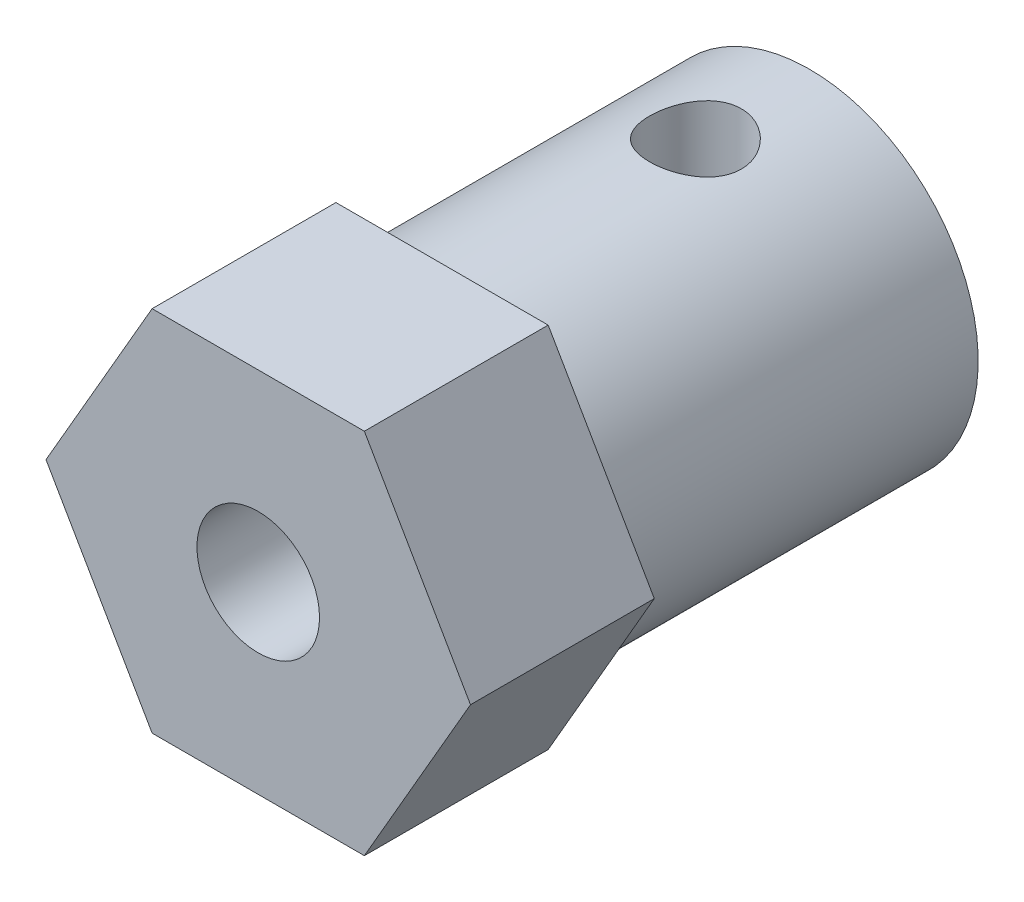
SolidWorks part; units mm, degrees
material "合金钢"
ref_plane "前视基准面" through (0, 0, 0) normal (0, 0, 1) x (1, 0, 0)
ref_plane "上视基准面" through (0, 0, 0) normal (0, 1, 0) x (1, 0, 0)
ref_plane "右视基准面" through (0, 0, 0) normal (1, 0, 0) x (0, 0, -1)
sketch "草图1" plane through (0, 0, 0) normal (0, 0, 1) x (1, 0, 0)
  line L0 (-3.4641, 6) -> (3.4641, 6)
  line L1 (3.4641, 6) -> (6.9282, 0)
  line L2 (6.9282, 0) -> (3.4641, -6)
  line L3 (3.4641, -6) -> (-3.4641, -6)
  line L4 (-3.4641, -6) -> (-6.9282, 0)
  line L5 (-6.9282, 0) -> (-3.4641, 6)
  circle A1 centre (0, 0) radius 2
extrude "凸台-拉伸1" add sketch "草图1" along normal blind 6
sketch "草图2" plane through (0, 0, 0) normal (0, 0, -1) x (-1, 0, 0)
  circle A0 centre (0, 0) radius 5.5
  circle A1 centre (0, 0) radius 3
extrude "凸台-拉伸2" add sketch "草图2" along normal blind 12
sketch "草图3" plane through (0, 0, 0) normal (0, 1, 0) x (1, 0, 0)
  circle A0 centre (0, 8.2699) radius 1.5
extrude "切除-拉伸1" cut sketch "草图3" against normal blind 20 from offset 10
